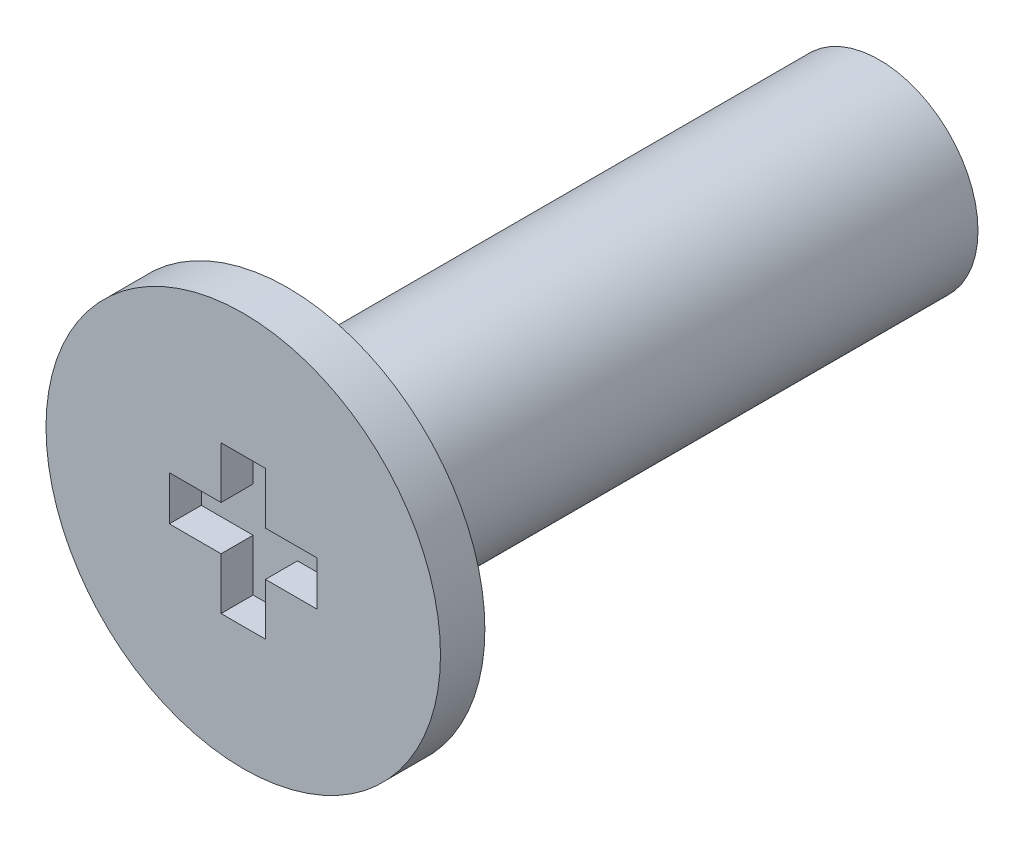
SolidWorks part; units mm, degrees
ref_plane "前视基准面" through (0, 0, 0) normal (0, 0, 1) x (1, 0, 0)
ref_plane "上视基准面" through (0, 0, 0) normal (0, 1, 0) x (1, 0, 0)
ref_plane "右视基准面" through (0, 0, 0) normal (1, 0, 0) x (0, 0, -1)
other "Configuration Table"
sketch "草图1" plane through (0, 0, 0) normal (0, 0, 1) x (1, 0, 0)
  circle A0 centre (0, 0) radius 2
extrude "标准杆径_头下长度" add sketch "草图1" against normal blind 12
sketch "草图2" plane through (0, 0, 0) normal (0, 0, 1) x (1, 0, 0)
  circle A0 centre (0, 0) radius 3.5
sketch "草图4" plane through (0, 0, 0) normal (0, 1, 0) x (1, 0, 0)
  line L0 (0, 0) -> (4.7, 0)
  line L1 (4.7, 0) -> (4.7, -0.2884)
  line L2 (0, -2.5) -> (0, 0)
  line L3 (0, 2) -> (0, -4.5) construction
  arc A0 (4.7, -0.2884) -> (0, -2.5) centre (0, 3.6) cw
sketch "草图5" plane through (0, 0, 0) normal (0, 0, 1) x (1, 0, 0)
  line L0 (-0.5, -2.15) -> (0.5, -2.15)
  line L1 (0.5, -2.15) -> (0.5, -0.5)
  line L2 (0.5, -0.5) -> (2.15, -0.5)
  line L3 (2.15, -0.5) -> (2.15, 0.5)
  line L4 (2.15, 0.5) -> (0.5, 0.5)
  line L5 (0.5, 0.5) -> (0.5, 2.15)
  line L6 (0.5, 2.15) -> (-0.5, 2.15)
  line L7 (-0.5, 2.15) -> (-0.5, 0.5)
  line L8 (-0.5, 0.5) -> (-2.15, 0.5)
  line L9 (-2.15, 0.5) -> (-2.15, -0.5)
  line L10 (-2.15, -0.5) -> (-0.5, -0.5)
  line L11 (-0.5, -0.5) -> (-0.5, -2.15)
sketch "草图6" plane through (0, 0, 0) normal (0, 1, 0) x (1, 0, 0)
  line L0 (0, 0) -> (4, 0)
  line L1 (4, 0) -> (4, -0.9)
  line L2 (4, -0.9) -> (0, -0.9)
  line L3 (0, -0.9) -> (0, 0)
  line L4 (0, 2) -> (0, -2.9) construction
revolve "已确认_十字槽超薄头" add sketch "草图6" angle 360 about L4
sketch "草图7" plane through (0, 0, 0) normal (0, 0, 1) x (1, 0, 0)
  line L0 (-0.45, -1.5) -> (0.45, -1.5)
  line L1 (0.45, -1.5) -> (0.45, -0.45)
  line L2 (0.45, -0.45) -> (1.5, -0.45)
  line L3 (1.5, -0.45) -> (1.5, 0.45)
  line L4 (1.5, 0.45) -> (0.45, 0.45)
  line L5 (0.45, 0.45) -> (0.45, 1.5)
  line L6 (0.45, 1.5) -> (-0.45, 1.5)
  line L7 (-0.45, 1.5) -> (-0.45, 0.45)
  line L8 (-0.45, 0.45) -> (-1.5, 0.45)
  line L9 (-1.5, 0.45) -> (-1.5, -0.45)
  line L10 (-1.5, -0.45) -> (-0.45, -0.45)
  line L11 (-0.45, -0.45) -> (-0.45, -1.5)
extrude "十字槽_PH2_简化" cut sketch "草图7" against normal blind 0.66 from offset 0.91
